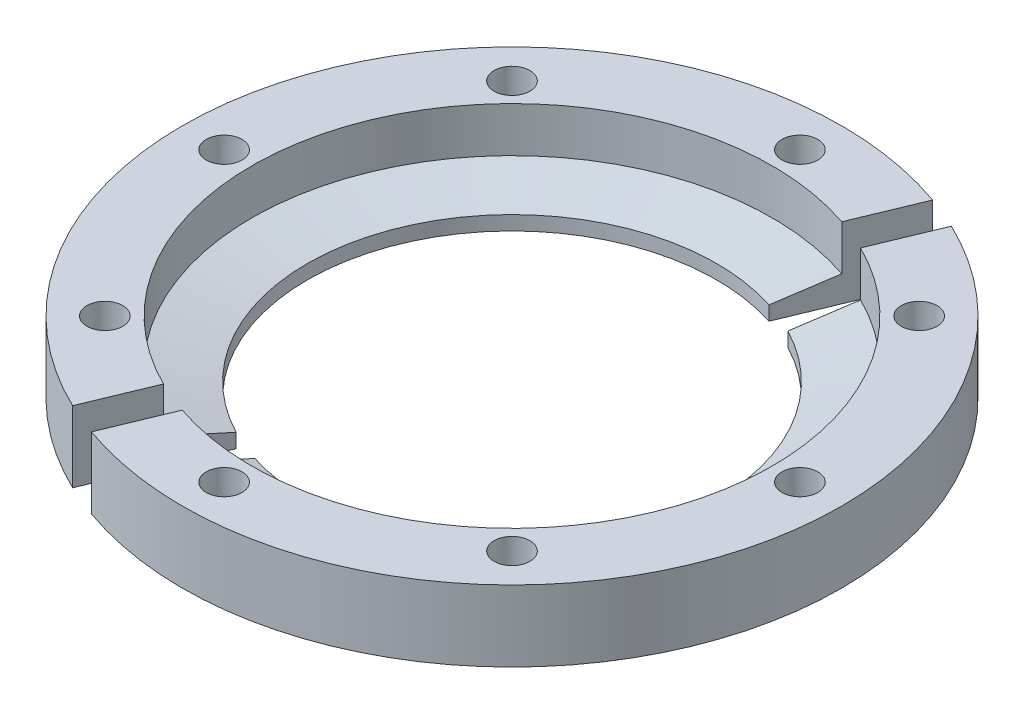
SolidWorks part; units mm, degrees
material "6061-T6 (SS)"
ref_plane "Front Plane" through (0, 0, 0) normal (0, 0, 1) x (1, 0, 0)
ref_plane "Top Plane" through (0, 0, 0) normal (0, 1, 0) x (1, 0, 0)
ref_plane "Right Plane" through (0, 0, 0) normal (1, 0, 0) x (0, 0, -1)
sketch "Sketch1" plane through (0, 0, 0) normal (0, 1, 0) x (1, 0, 0)
  circle A0 centre (0, 0) radius 47.5
  dimension "D1" = 95
extrude "Boss-Extrude1" add sketch "Sketch1" along normal blind 10.25
sketch "Sketch2" plane through (0, 0, 0) normal (0, 0, 1) x (1, 0, 0)
  line L0 (29.5, 0) -> (29.5, 2.0495)
  line L1 (-47.5, 0) -> (47.5, 0) construction
  line L2 (29.5, 2.0495) -> (37.5, 3.75)
  line L3 (37.5, 3.75) -> (37.5, 10.25)
  line L4 (47.5, 10.25) -> (-47.5, 10.25) construction
  line L5 (37.5, 10.25) -> (0, 10.25)
  line L6 (0, 10.25) -> (0, 0)
  line L7 (0, 0) -> (29.5, 0)
  line L8 (0, 0) -> (0, -3.744) construction
  dimension "D1" = 75
  dimension "D2" = 6.5
  dimension "D3" = 59
  dimension "D4" = 78
revolve "Cut-Revolve1" cut sketch "Sketch2" angle 360 about L8
sketch "Sketch3" plane through (0, 10.25, 0) normal (0, 1, 0) x (1, 0, 0)
  line L0 (0, 0) -> (0, -3.5728) construction
  circle A0 centre (41.5, 0) radius 2.585
  dimension "D1" = 83
  dimension "D2" = 5.17
extrude "Cut-Extrude1" cut sketch "Sketch3" against normal through all
pattern_circular "CirPattern1" count 8 over 360 about axis through (0, 0, 0) along (0, 1, 0) of "Cut-Extrude1"
sketch "Sketch4" plane through (0, 10.25, 0) normal (0, 1, 0) x (1, 0, 0)
  line L0 (15.8426, 44.7802) -> (-20.462, -42.8667)
  line L1 (-15.8426, -44.7802) -> (20.462, 42.8667)
  line L2 (0, 0) -> (2.2971, 5.5458) construction
  line L3 (2.2971, 5.5458) -> (4.6068, 4.5891) construction
  line L4 (2.2971, 5.5458) -> (-0.0126, 6.5025) construction
  line L5 (0, 0) -> (11.0132, 0) construction
  circle A0 centre (0, 0) radius 47.5 construction
  arc A1 (-20.462, -42.8667) -> (-15.8426, -44.7802) centre (0, 0) ccw
  arc A2 (20.462, 42.8667) -> (15.8426, 44.7802) centre (0, 0) ccw
  dimension "D1" = 5
  dimension "D2" = 67.5
extrude "Cut-Extrude2" cut sketch "Sketch4" against normal through all
sketch "Sketch5" plane through (0, 0, 0) normal (0, -1, 0) x (1, 0, 0)
  circle A0 centre (41.5, 0) radius 2.7
  circle A1 centre (41.5, 0) radius 4.93
  dimension "D1" = 5.4
  dimension "D2" = 9.86
ref_plane "Plane1" through (0, 8.75, 0) normal (0, 1, 0) x (1, 0, 0)
